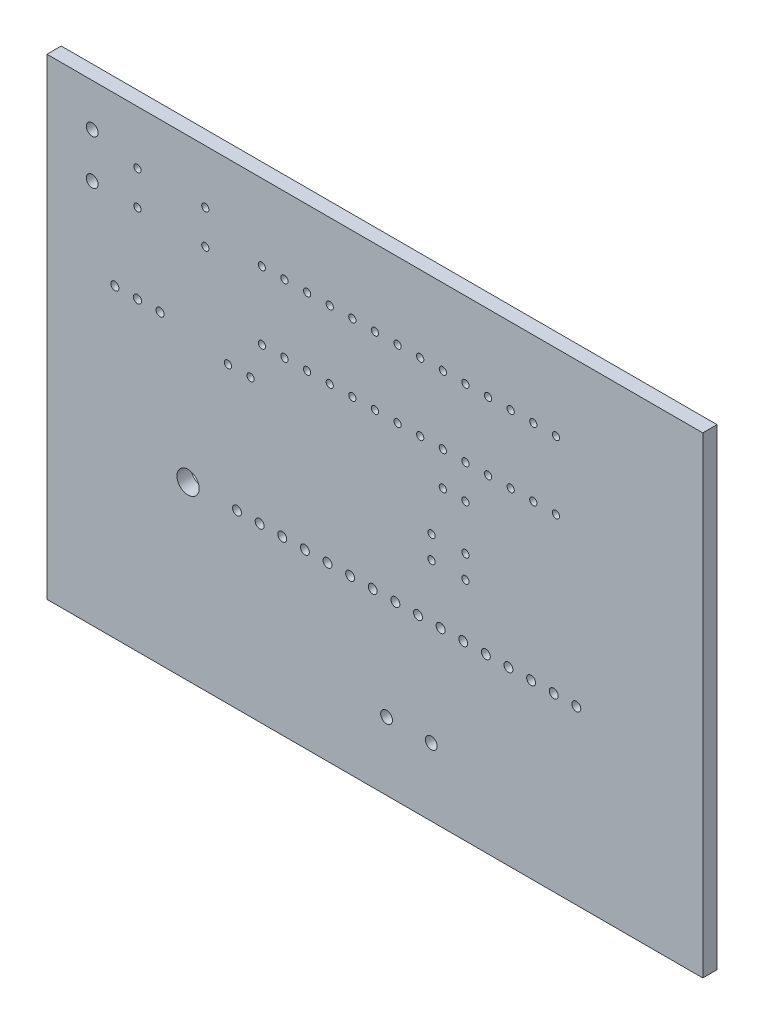
SolidWorks part; units mm, degrees
ref_plane "Front Plane" through (0, 0, 0) normal (0, 0, 1) x (1, 0, 0)
ref_plane "Top Plane" through (0, 0, 0) normal (0, 1, 0) x (1, 0, 0)
ref_plane "Right Plane" through (0, 0, 0) normal (1, 0, 0) x (0, 0, -1)
ref_plane "Dielectric_Layer Layer 1" through (0, 0, 1.6) normal (0, 0, 1) x (1, 0, 0)
sketch "Sketch1" plane through (0, 0, 0) normal (0, 0, 1) x (1, 0, 0)
  line L0 (44.45, 16.51) -> (118.09, 16.51)
  line L1 (118.09, 16.51) -> (118.09, 69.52)
  line L2 (118.09, 69.52) -> (44.45, 69.52)
  line L3 (44.45, 69.52) -> (44.45, 16.51)
extrude "Board_Outline" add sketch "Sketch1" along normal blind 1.6 separate body
sketch "Sketch2" plane through (0, 0, 0) normal (0, 0, 1) x (1, 0, 0)
  circle A0 centre (60.29, 4.82) radius 1.25
  circle A1 centre (135.29, 4.82) radius 1.25
  circle A2 centre (60.29, 35.82) radius 1.25
  circle A3 centre (135.29, 35.82) radius 1.25
extrude "NPTH" cut sketch "Sketch2" along normal through all
sketch "Sketch3" plane through (0, 0, 0) normal (0, 0, 1) x (1, 0, 0)
  circle A0 centre (88.9, 49.53) radius 0.405
  circle A1 centre (91.44, 49.53) radius 0.405
  circle A2 centre (91.44, 41.91) radius 0.405
  circle A3 centre (91.44, 44.45) radius 0.405
  circle A4 centre (87.63, 41.91) radius 0.405
  circle A5 centre (87.63, 44.45) radius 0.405
  circle A6 centre (52.07, 50.8) radius 0.455
  circle A7 centre (54.61, 50.8) radius 0.455
  circle A8 centre (57.15, 50.8) radius 0.455
  circle A9 centre (65.79, 35.82) radius 0.5
  circle A10 centre (68.33, 35.82) radius 0.5
  circle A11 centre (70.87, 35.82) radius 0.5
  circle A12 centre (73.41, 35.82) radius 0.5
  circle A13 centre (75.95, 35.82) radius 0.5
  circle A14 centre (78.49, 35.82) radius 0.5
  circle A15 centre (81.03, 35.82) radius 0.5
  circle A16 centre (83.57, 35.82) radius 0.5
  circle A17 centre (86.11, 35.82) radius 0.5
  circle A18 centre (88.65, 35.82) radius 0.5
  circle A19 centre (91.19, 35.82) radius 0.5
  circle A20 centre (93.73, 35.82) radius 0.5
  circle A21 centre (96.27, 35.82) radius 0.5
  circle A22 centre (98.81, 35.82) radius 0.5
  circle A23 centre (101.35, 35.82) radius 0.5
  circle A24 centre (103.89, 35.82) radius 0.5
  circle A25 centre (68.58, 53.34) radius 0.405
  circle A26 centre (71.12, 53.34) radius 0.405
  circle A27 centre (73.66, 53.34) radius 0.405
  circle A28 centre (76.2, 53.34) radius 0.405
  circle A29 centre (78.74, 53.34) radius 0.405
  circle A30 centre (81.28, 53.34) radius 0.405
  circle A31 centre (83.82, 53.34) radius 0.405
  circle A32 centre (86.36, 53.34) radius 0.405
  circle A33 centre (88.9, 53.34) radius 0.405
  circle A34 centre (91.44, 53.34) radius 0.405
  circle A35 centre (93.98, 53.34) radius 0.405
  circle A36 centre (96.52, 53.34) radius 0.405
  circle A37 centre (99.06, 53.34) radius 0.405
  circle A38 centre (101.6, 53.34) radius 0.405
  circle A39 centre (101.6, 60.96) radius 0.405
  circle A40 centre (99.06, 60.96) radius 0.405
  circle A41 centre (96.52, 60.96) radius 0.405
  circle A42 centre (93.98, 60.96) radius 0.405
  circle A43 centre (91.44, 60.96) radius 0.405
  circle A44 centre (88.9, 60.96) radius 0.405
  circle A45 centre (86.36, 60.96) radius 0.405
  circle A46 centre (83.82, 60.96) radius 0.405
  circle A47 centre (81.28, 60.96) radius 0.405
  circle A48 centre (78.74, 60.96) radius 0.405
  circle A49 centre (76.2, 60.96) radius 0.405
  circle A50 centre (73.66, 60.96) radius 0.405
  circle A51 centre (71.12, 60.96) radius 0.405
  circle A52 centre (68.58, 60.96) radius 0.405
  circle A53 centre (54.61, 63.5) radius 0.405
  circle A54 centre (62.23, 63.5) radius 0.405
  circle A55 centre (62.23, 59.69) radius 0.405
  circle A56 centre (54.61, 59.69) radius 0.405
  circle A57 centre (67.31, 49.53) radius 0.405
  circle A58 centre (64.77, 49.53) radius 0.405
  circle A59 centre (49.53, 64.74) radius 0.66
  circle A60 centre (49.53, 59.72) radius 0.66
  circle A61 centre (87.6, 24.13) radius 0.66
  circle A62 centre (82.58, 24.13) radius 0.66
extrude "PTH" cut sketch "Sketch3" along normal through all
